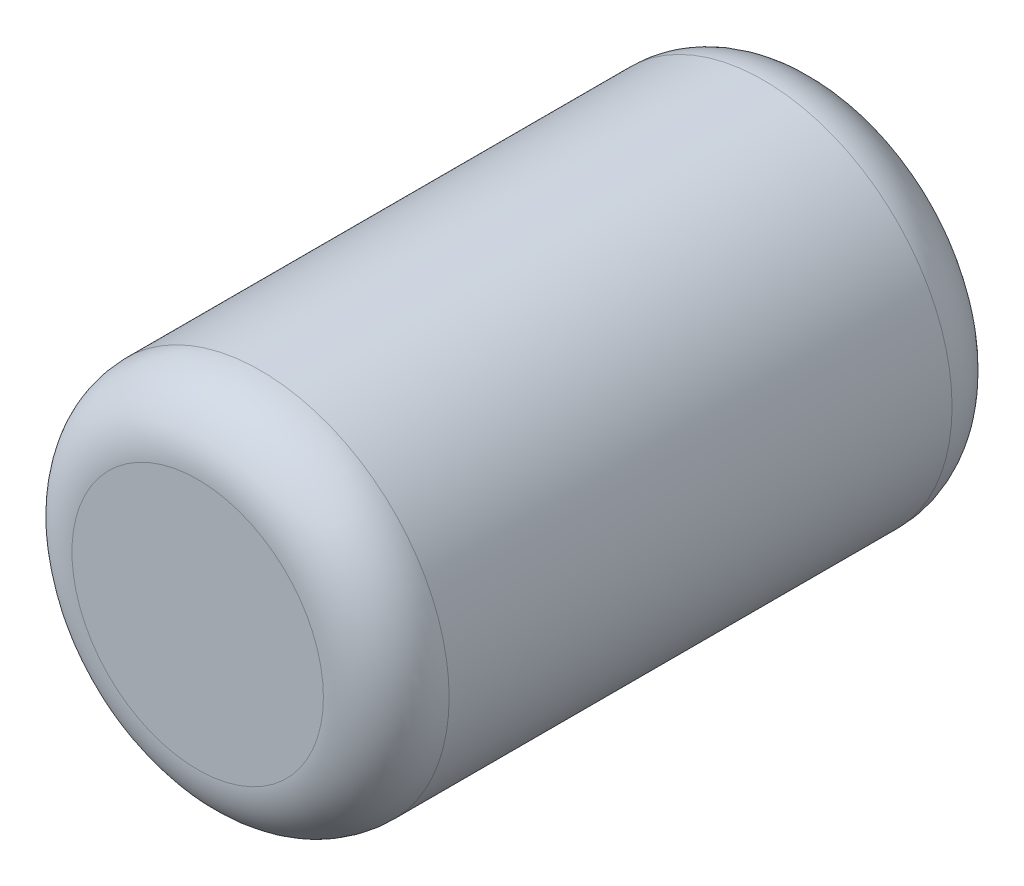
SolidWorks part; units mm, degrees
ref_plane "Front Plane" through (0, 0, 0) normal (0, 0, 1) x (1, 0, 0)
ref_plane "Top Plane" through (0, 0, 0) normal (0, 1, 0) x (1, 0, 0)
ref_plane "Right Plane" through (0, 0, 0) normal (1, 0, 0) x (0, 0, -1)
sketch "Sketch2" plane through (0, 0, 0) normal (0, 0, 1) x (1, 0, 0)
  circle A0 centre (0, 0) radius 9
  dimension "D1" = 18
extrude "Boss-Extrude1" add sketch "Sketch2" along normal blind 30
ref_point "Point1"
ref_point "Point2"
fillet "Fillet1" radius 3 2 edges at (9, 0, 30) (9, 0, 0)
